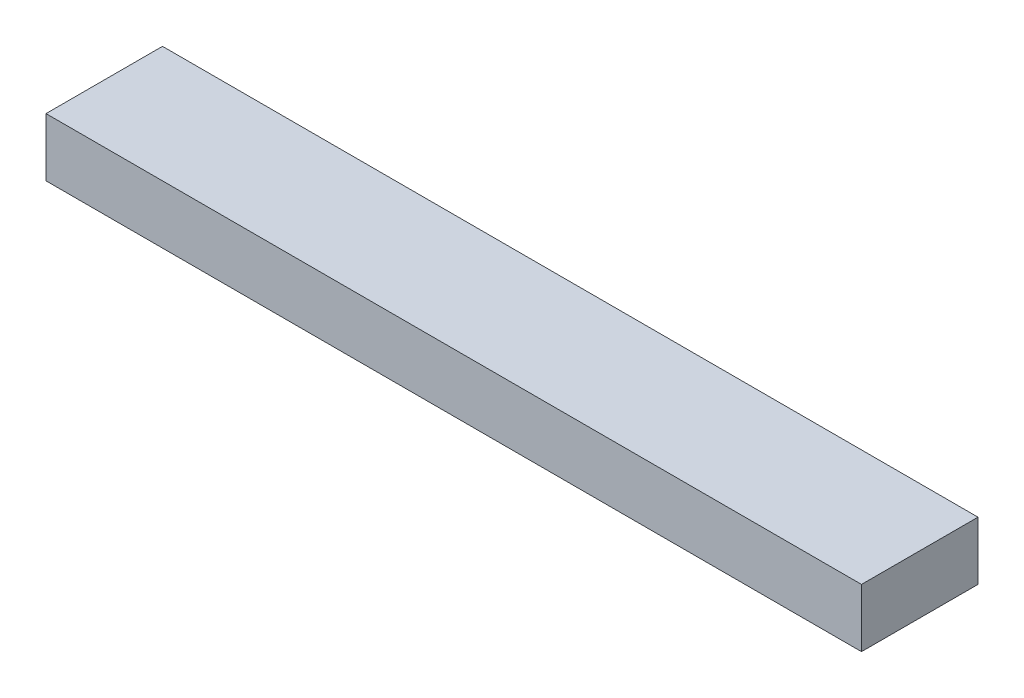
SolidWorks part; units mm, degrees
ref_plane "Front Plane" through (0, 0, 0) normal (0, 0, 1) x (1, 0, 0)
ref_plane "Top Plane" through (0, 0, 0) normal (0, 1, 0) x (1, 0, 0)
ref_plane "Right Plane" through (0, 0, 0) normal (1, 0, 0) x (0, 0, -1)
sketch "Sketch1" plane through (0, 0, 0) normal (0, 1, 0) x (1, 0, 0)
  line L1 (0, 0) -> (177.8, 0)
  line L2 (0, 0) -> (0, 25.4)
  line L3 (0, 25.4) -> (177.8, 25.4)
  line L4 (177.8, 0) -> (177.8, 25.4)
  dimension "D1" = 25.4
  dimension "D2" = 177.8
extrude "Boss-Extrude1" add sketch "Sketch1" along normal blind 12.7
